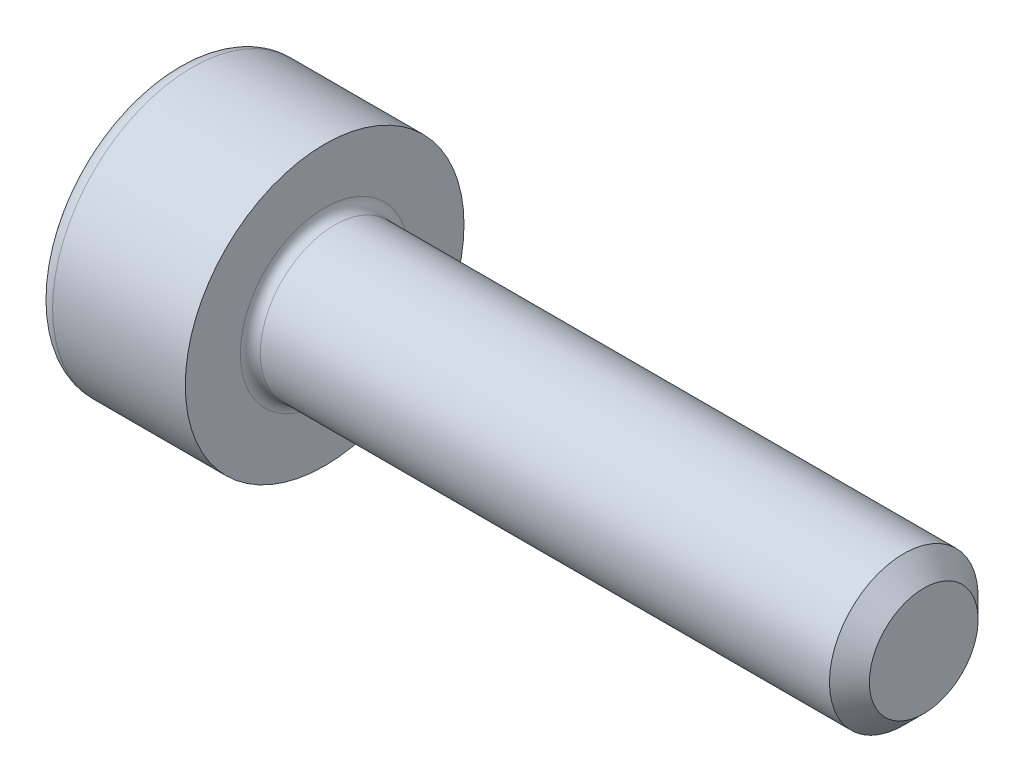
SolidWorks part; units mm, degrees
ref_plane "Спереди" through (0, 0, 0) normal (0, 0, 1) x (1, 0, 0)
ref_plane "Сверху" through (0, 0, 0) normal (0, 1, 0) x (1, 0, 0)
ref_plane "Справа" through (0, 0, 0) normal (1, 0, 0) x (0, 0, -1)
sketch "Sketch1" plane through (0, 0, 0) normal (0, 0, 1) x (1, 0, 0)
  line L0 (0, 0) -> (1.4887, 0)
  line L1 (1.4887, 0) -> (1.4887, 1.3957)
  line L2 (1.4887, 1.3957) -> (0, 1.3957)
  line L3 (0, 1.3957) -> (0, 0)
  line L4 (1.4887, 0) -> (7.4887, 0)
  line L5 (7.4887, 0) -> (7.4887, 0.7444)
  line L6 (7.4887, 0.7444) -> (1.4887, 0.7444)
  dimension "D1" = 6
revolve "Revolve1" add sketch "Sketch1" angle 360 about L0
fillet "Fillet1" radius 0.1 1 edges at (1.4887, 0, 0.7444)
fillet "Fillet2" radius 0.16 1 edges at (0, 0, 1.3957)
chamfer "Chamfer1" distance 0.2 angle 45 1 edges at (7.4887, 0, 0.7444)
sketch "Sketch2" plane through (0, 0, 0) normal (-1, 0, 0) x (0, 0, 1)
  line L1 (0, 0.8776) -> (-0.76, 0.4388)
  line L2 (-0.76, 0.4388) -> (-0.76, -0.4388)
  line L3 (-0.76, -0.4388) -> (0, -0.8776)
  line L4 (0, -0.8776) -> (0.76, -0.4388)
  line L5 (0.76, -0.4388) -> (0.76, 0.4388)
  line L6 (0.76, 0.4388) -> (0, 0.8776)
  circle A0 centre (0, 0) radius 0.76 construction
extrude "Extrude1" cut sketch "Sketch2" against normal blind 0.7
